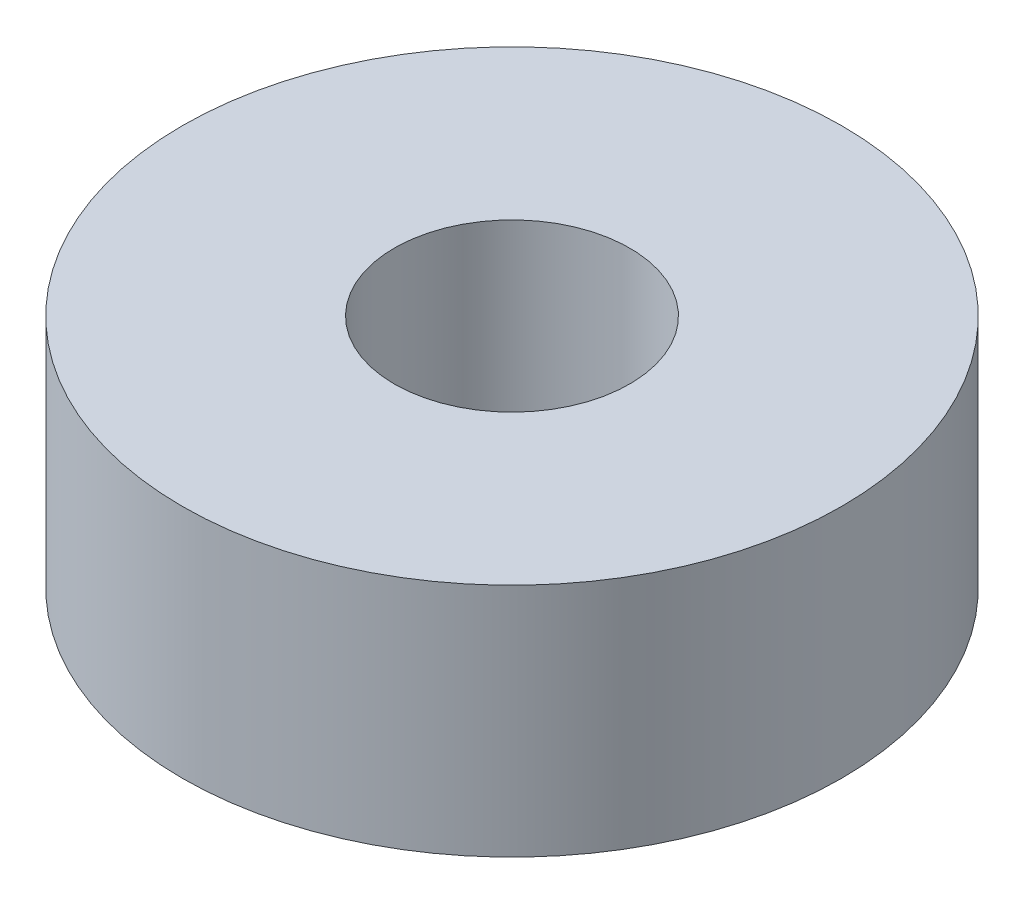
SolidWorks part; units mm, degrees
ref_plane "Front Plane" through (0, 0, 0) normal (0, 0, 1) x (1, 0, 0)
ref_plane "Top Plane" through (0, 0, 0) normal (0, 1, 0) x (1, 0, 0)
ref_plane "Right Plane" through (0, 0, 0) normal (1, 0, 0) x (0, 0, -1)
sketch "Sketch1" plane through (0, 0, 0) normal (0, 1, 0) x (1, 0, 0)
  circle A0 centre (0, 0) radius 7
  circle A1 centre (0, 0) radius 2.5
  dimension "D1" = 14
  dimension "D2" = 5
extrude "Boss-Extrude1" add sketch "Sketch1" along normal blind 5
